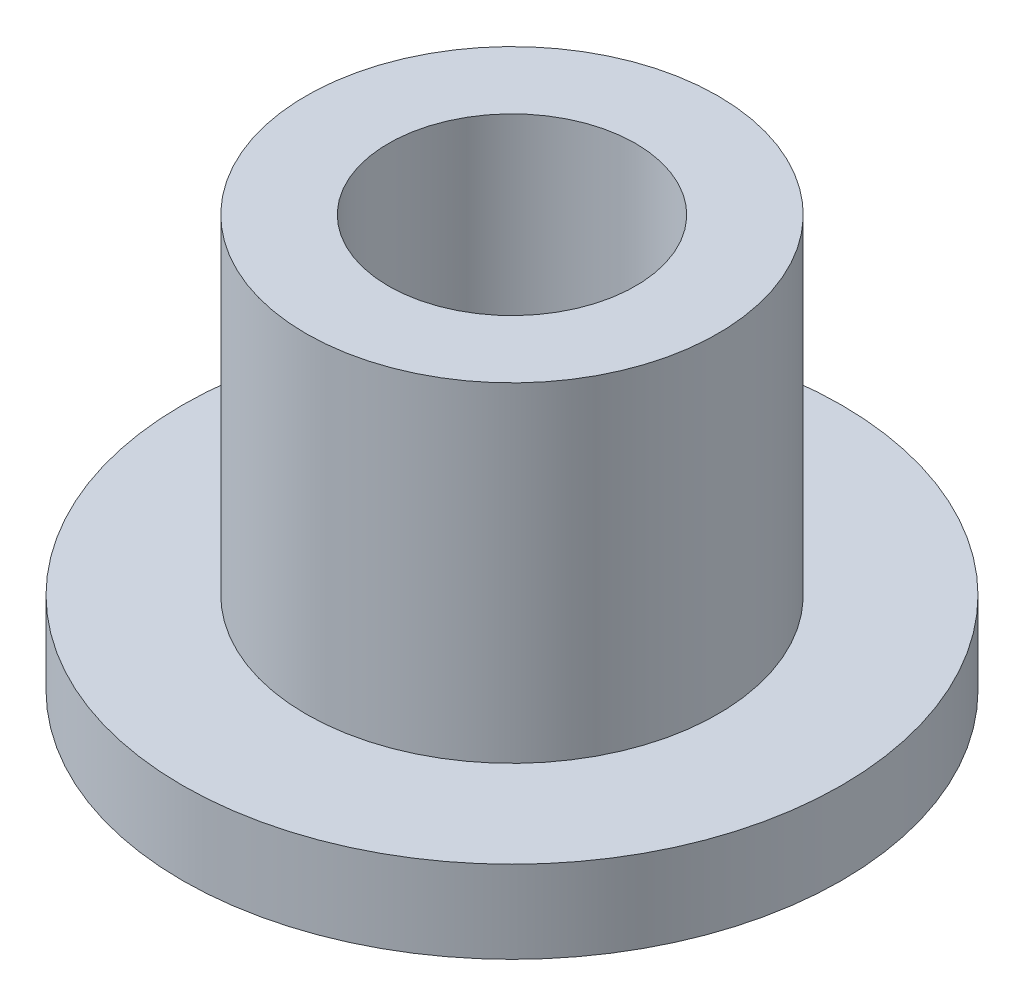
SolidWorks part; units mm, degrees
ref_plane "Płaszczyzna przednia" through (0, 0, 0) normal (0, 0, 1) x (1, 0, 0)
ref_plane "Płaszczyzna górna" through (0, 0, 0) normal (0, 1, 0) x (1, 0, 0)
ref_plane "Płaszczyzna prawa" through (0, 0, 0) normal (1, 0, 0) x (0, 0, -1)
sketch "Szkic1" plane through (0, 0, 0) normal (0, 1, 0) x (1, 0, 0)
  circle A0 centre (0, 0) radius 1.5
  circle A1 centre (0, 0) radius 4
  dimension "D1" = 3
  dimension "D2" = 8
extrude "Dodanie-wyciągnięcie1" add sketch "Szkic1" along normal blind 2
sketch "Szkic2" plane through (0, 2, 0) normal (0, 1, 0) x (1, 0, 0)
  circle A0 centre (0, 0) radius 1.5
  circle A1 centre (0, 0) radius 2.5
  dimension "D1" = 5
extrude "Dodanie-wyciągnięcie2" add sketch "Szkic2" along normal blind 4
chamfer "Sfazowanie1" distance 1 angle 60 1 edges at (0, 0, 4)
